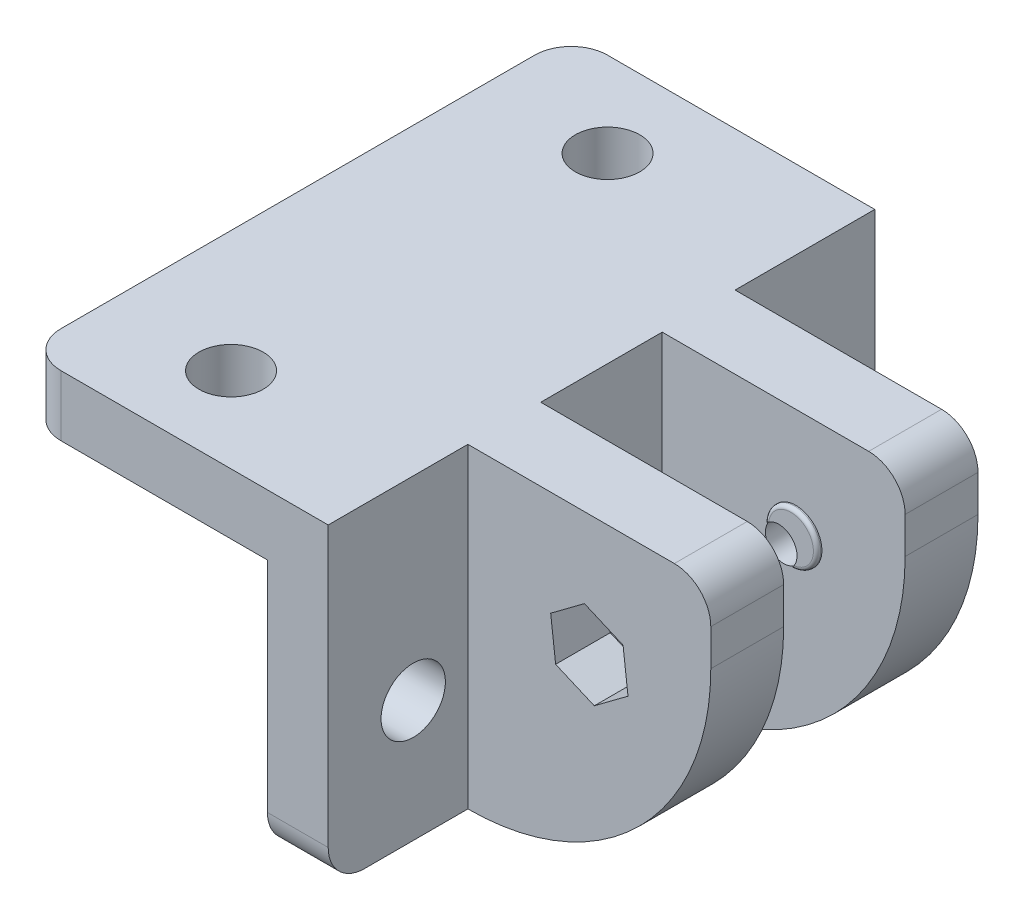
SolidWorks part; units mm, degrees
ref_plane "Front Plane" through (0, 0, 0) normal (0, 0, 1) x (1, 0, 0)
ref_plane "Top Plane" through (0, 0, 0) normal (0, 1, 0) x (1, 0, 0)
ref_plane "Right Plane" through (0, 0, 0) normal (1, 0, 0) x (0, 0, -1)
sketch "Sketch1" plane through (0, 0, 0) normal (1, 0, 0) x (0, 0, -1)
  line L1 (0, 0) -> (45, 0)
  line L2 (0, 0) -> (0, 5)
  line L3 (0, 5) -> (45, 5)
  line L4 (45, 0) -> (45, 5)
  dimension "D1" = 45
  dimension "D2" = 5
extrude "Boss-Extrude1" add sketch "Sketch1" against normal blind 20
sketch "Sketch2" plane through (0, 5, 0) normal (0, 1, 0) x (1, 0, 0)
  line L1 (0, 0) -> (5, 0)
  line L2 (0, 0) -> (0, 45)
  line L3 (0, 45) -> (5, 45)
  line L4 (5, 0) -> (5, 45)
  dimension "D1" = 5
  dimension "D2" = 45
extrude "Boss-Extrude2" add sketch "Sketch2" against normal blind 26
sketch "Sketch3" plane through (0, 5, 0) normal (0, 1, 0) x (1, 0, 0)
  line L0 (-20, 45) -> (-20, 0) construction
  line L1 (-20, 0) -> (5, 0) construction
  line L2 (-20, 45) -> (5, 45) construction
  circle A0 centre (-10, 7) radius 2.65
  circle A1 centre (-10, 38) radius 2.65
  dimension "D3" = 5.3
  dimension "D1" = 10
  dimension "D2" = 7
  dimension "D4" = 7
  dimension "D5" = 10
extrude "Cut-Extrude1" cut sketch "Sketch3" against normal blind 26
sketch "Sketch4" plane through (5, 0, 0) normal (1, 0, 0) x (0, 0, -1)
  line L0 (0, -21) -> (0, 5) construction
  line L1 (0, -21) -> (45, -21) construction
  line L2 (45, -21) -> (45, 5) construction
  circle A0 centre (7, -11) radius 2.65
  circle A1 centre (38, -11) radius 2.65
  dimension "D3" = 5.3
  dimension "D1" = 7
  dimension "D2" = 10
  dimension "D4" = 10
  dimension "D5" = 7
extrude "Cut-Extrude2" cut sketch "Sketch4" against normal blind 26
fillet "Fillet1" radius 3 4 edges at (2.5, -21, 0) (2.5, -21, -45) (-20, 2.5, -45) (-20, 2.5, 0)
sketch "Sketch5" plane through (5, 0, 0) normal (1, 0, 0) x (0, 0, -1)
  line L0 (0, 5) -> (45, 5) construction
  line L1 (33.5, 5) -> (27.5, 5)
  line L2 (33.5, 5) -> (33.5, -21)
  line L3 (33.5, -21) -> (27.5, -21)
  line L4 (27.5, 5) -> (27.5, -21)
  line L5 (3, -21) -> (42, -21) construction
  line L6 (0, -18) -> (0, 5) construction
  line L7 (11.5, -21) -> (17.5, -21)
  line L8 (11.5, -21) -> (11.5, 5)
  line L9 (11.5, 5) -> (17.5, 5)
  line L10 (17.5, -21) -> (17.5, 5)
  line L11 (45, -18) -> (45, 5) construction
  dimension "D1" = 6
  dimension "D2" = 6
  dimension "D3" = 11.5
  dimension "D4" = 11.5
extrude "Boss-Extrude3" add sketch "Sketch5" along normal blind 20
sketch "Sketch8" plane through (0, 0, -27.5) normal (0, 0, 1) x (1, 0, 0)
  circle A0 centre (16, -4) radius 2.15
  dimension "D1" = 4.3
extrude "Boss-Extrude6" add sketch "Sketch8" along normal blind 0.4
sketch "Sketch7" plane through (0, 0, -17.5) normal (0, 0, -1) x (-1, 0, 0)
  circle A0 centre (-16, -4) radius 2.15
  dimension "D1" = 4.3
extrude "Boss-Extrude5" add sketch "Sketch7" along normal blind 0.4
sketch "Sketch6" plane through (0, 0, -11.5) normal (0, 0, 1) x (1, 0, 0)
  line L1 (25, 5) -> (5, 5) construction
  line L2 (5, 5) -> (5, -21) construction
  circle A0 centre (15, -5) radius 1.5
  dimension "D3" = 3
  dimension "D1" = 10
  dimension "D2" = 10
extrude "Cut-Extrude3" cut sketch "Sketch6" against normal through all
fillet "Fillet2" radius 20 2 edges at (25, -21, -14.5) (25, -21, -30.5)
fillet "Fillet3" radius 3 2 edges at (25, 5, -14.5) (25, 5, -30.5)
fillet "Fillet4" radius 0.3 1 edges at (17.5203, -2.4797, -27.1)
fillet "Fillet5" radius 0.3 1 edges at (17.5203, -2.4797, -17.9)
sketch "Sketch9" plane through (0, 0, -11.5) normal (0, 0, 1) x (1, 0, 0)
  line L1 (14.5926, -1.5599) -> (11.8171, -3.6328)
  line L2 (11.8171, -3.6328) -> (12.2245, -7.0729)
  line L3 (12.2245, -7.0729) -> (15.4074, -8.4401)
  line L4 (15.4074, -8.4401) -> (18.1829, -6.3672)
  line L5 (18.1829, -6.3672) -> (17.7755, -2.9271)
  line L6 (17.7755, -2.9271) -> (14.5926, -1.5599)
  circle A0 centre (15, -5) radius 3 construction
  dimension "D1" = 6
extrude "Cut-Extrude4" cut sketch "Sketch9" against normal blind 4.5
